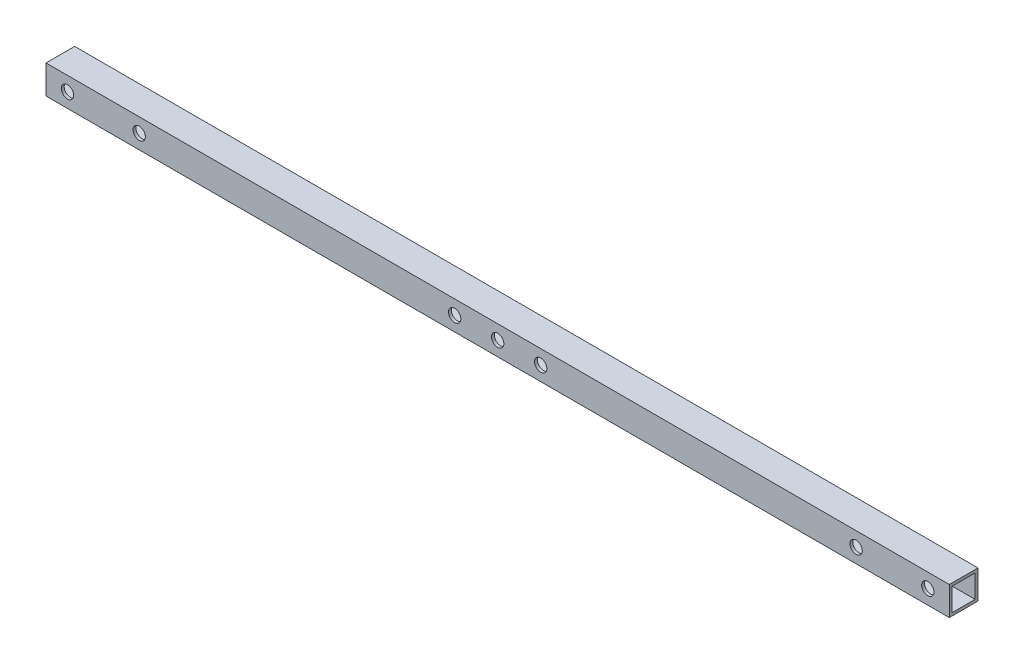
SolidWorks part; units mm, degrees
material "5052-H34"
ref_plane "正面" through (0, 0, 0) normal (0, 0, 1) x (1, 0, 0)
ref_plane "平面" through (0, 0, 0) normal (0, 1, 0) x (1, 0, 0)
ref_plane "右側面" through (0, 0, 0) normal (1, 0, 0) x (0, 0, -1)
sketch "ｽｹｯﾁ1" plane through (0, 0, 0) normal (1, 0, 0) x (0, 0, -1)
  line L1 (-5, 5) -> (5, 5)
  line L2 (-5, 5) -> (-5, -5)
  line L3 (-5, -5) -> (5, -5)
  line L4 (5, 5) -> (5, -5)
  line L5 (-5, 5) -> (5, -5) construction
  line L6 (-5, -5) -> (5, 5) construction
  point P0 (0, 0)
  dimension "D1" = 10
  dimension "D2" = 10
extrude "押し出し-薄板1" add sketch "ｽｹｯﾁ1" along normal blind 315 thin
sketch "ｽｹｯﾁ2" plane through (0, 0, 5) normal (0, 0, 1) x (1, 0, 0)
  line L0 (157.5, 5) -> (157.5, -5) construction
  line L1 (315, 5) -> (0, 5) construction
  line L2 (315, -5) -> (0, -5) construction
  line L3 (315, 0) -> (282.5, 0) construction
  line L4 (315, 5) -> (315, -5) construction
  line L5 (157.5, 0) -> (172.5, 0) construction
  circle A0 centre (307.5, 0) radius 2.15
  circle A1 centre (282.5, 0) radius 2.15
  circle A2 centre (7.5, 0) radius 2.15
  circle A3 centre (32.5, 0) radius 2.15
  circle A4 centre (172.5, 0) radius 2.15
  circle A5 centre (157.5, 0) radius 2.15
  circle A6 centre (142.5, 0) radius 2.15
  dimension "D1" = 4.3
  dimension "D2" = 7.5
  dimension "D3" = 25
  dimension "D4" = 30
extrude "ｶｯﾄ - 押し出し1" cut sketch "ｽｹｯﾁ2" against normal through all
